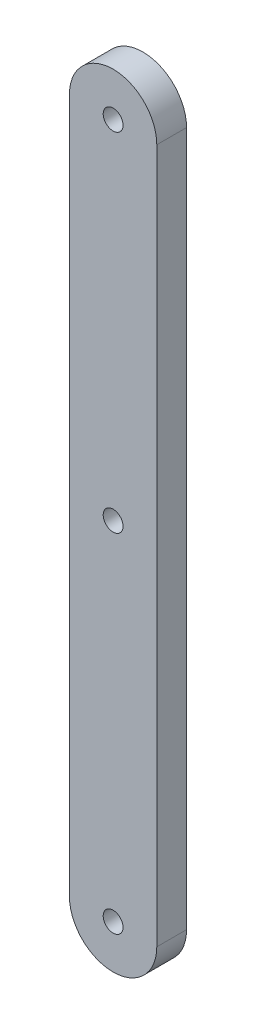
SolidWorks part; units mm, degrees
ref_plane "Front Plane" through (0, 0, 0) normal (1, 0, 0) x (0, 1, 0)
ref_plane "Top Plane" through (0, 0, 0) normal (0, 0, 1) x (0, 1, 0)
ref_plane "Right Plane" through (0, 0, 0) normal (0, 1, 0) x (-1, 0, 0)
sketch "Sketch1" plane through (0, 0, 0) normal (0, 0, 1) x (0, 1, 0)
  line L0 (-35, 0) -> (35, 0) construction
  line L1 (-35, 4.4) -> (35, 4.4)
  line L2 (-35, -4.4) -> (35, -4.4)
  arc A0 (-35, 4.4) -> (-35, -4.4) centre (-35, 0) ccw
  arc A1 (35, -4.4) -> (35, 4.4) centre (35, 0) ccw
  circle A2 centre (-35, 0) radius 4.4
  circle A3 centre (35, 0) radius 4.4
  point P2 (0, 0)
  dimension "D1" = 8.8
  dimension "D2" = 70
extrude "Boss-Extrude1" add sketch "Sketch1" along normal blind 3
sketch "Sketch6" plane through (0, 0, 3) normal (0, 0, 1) x (1, 0, 0)
  circle A0 centre (0, 35) radius 1
  circle A1 centre (0, -35) radius 1
  circle A2 centre (0, 0) radius 1
  dimension "D1" = 2
  dimension "D2" = 2
extrude "Cut-Extrude1" cut sketch "Sketch6" against normal blind 3
chamfer "Chamfer1" distance 1.25 angle 45 3 edges at (1, 35, 0) (1, -35, 0) (1, 0, 0)
